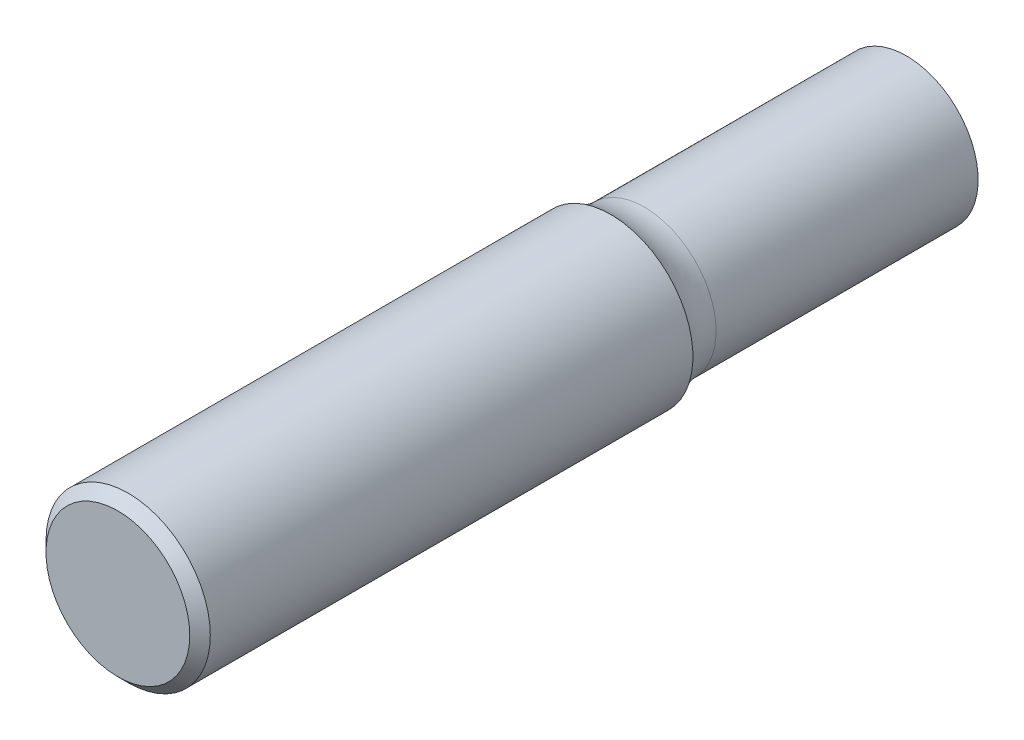
SolidWorks part; units mm, degrees
material "O1 Steel"
ref_plane "Alzado" through (0, 0, 0) normal (0, 0, 1) x (1, 0, 0)
ref_plane "Planta" through (0, 0, 0) normal (0, 1, 0) x (1, 0, 0)
ref_plane "Vista lateral" through (0, 0, 0) normal (1, 0, 0) x (0, 0, -1)
sketch "Croquis1" plane through (0, 0, 0) normal (1, 0, 0) x (0, 0, -1)
  line L0 (127, 0) -> (-127, 0) construction
  line L1 (-15.24, 0) -> (-15.24, 3.175)
  line L2 (-15.24, 3.175) -> (3.81, 3.175)
  line L4 (5.1111, 2.7686) -> (15.24, 2.7686)
  line L5 (15.24, 2.7686) -> (15.24, 0)
  line L6 (15.24, 0) -> (-15.24, 0)
  arc A0 (3.81, 3.175) -> (5.1111, 2.7686) centre (5.1111, 5.0546) ccw
  dimension "D6" = 2.286
  dimension "D1" = 254
  dimension "D2" = 6.35
  dimension "D3" = 30.48
  dimension "D4" = 19.05
  dimension "D5" = 5.5372
revolve "Revolución1" add sketch "Croquis1" angle 360 about L0
sketch "Croquis4" plane through (0, 0, 0) normal (1, 0, 0) x (0, 0, -1)
  line L0 (15.24, 0) -> (-15.24, 0) construction
  line L1 (15.24, -2.7686) -> (15.24, 2.7686) construction
  line L2 (-15.24, 3.175) -> (-15.24, -3.175) construction
  line L4 (14.732, 0) -> (15.24, 0)
  line L5 (15.24, 0) -> (15.24, 1.7227)
  arc A1 (14.732, 0) -> (15.24, 1.7227) centre (17.907, 0) cw
  dimension "D1" = 3.175
  dimension "D2" = 0.508
revolve "Cortar-Revolución1" cut sketch "Croquis4" angle 360 about L0
chamfer "Chaflán1" distance 0.3969 angle 45 1 edges at (-3.175, 0, 15.24)
